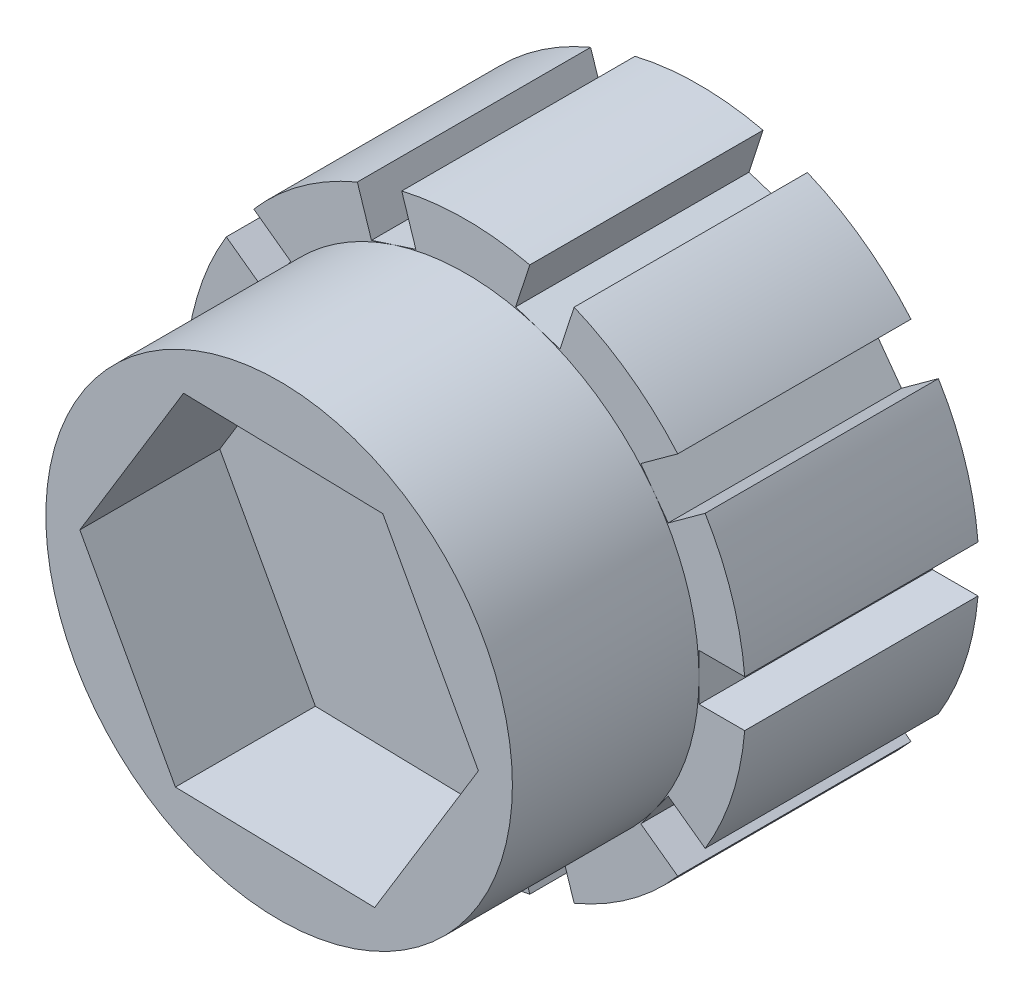
SolidWorks part; units mm, degrees
ref_plane "Front Plane" through (0, 0, 0) normal (0, 0, 1) x (1, 0, 0)
ref_plane "Top Plane" through (0, 0, 0) normal (0, 1, 0) x (1, 0, 0)
ref_plane "Right Plane" through (0, 0, 0) normal (1, 0, 0) x (0, 0, -1)
sketch "Sketch1" plane through (0, 0, 0) normal (0, 0, 1) x (1, 0, 0)
  circle A0 centre (0, 0) radius 6
  dimension "D1" = 12
extrude "Boss-Extrude1" add sketch "Sketch1" along normal blind 5
sketch "Sketch2" plane through (0, 0, 5) normal (0, 0, 1) x (1, 0, 0)
  circle A0 centre (0, 0) radius 5
  dimension "D1" = 10
extrude "Boss-Extrude2" add sketch "Sketch2" along normal blind 4
sketch "Sketch3" plane through (0, 0, 9) normal (0, 0, 1) x (1, 0, 0)
  line L1 (2.0482, -3.7494) -> (4.2712, -0.1009)
  line L2 (4.2712, -0.1009) -> (2.223, 3.6485)
  line L3 (2.223, 3.6485) -> (-2.0482, 3.7494)
  line L4 (-2.0482, 3.7494) -> (-4.2712, 0.1009)
  line L5 (-4.2712, 0.1009) -> (-2.223, -3.6485)
  line L6 (-2.223, -3.6485) -> (2.0482, -3.7494)
  circle A0 centre (0, 0) radius 3.7 construction
  dimension "D1" = 7.4
extrude "Cut-Extrude1" cut sketch "Sketch3" against normal blind 3
sketch "Sketch4" plane through (0, 0, 0) normal (0, 0, -1) x (-1, 0, 0)
  line L0 (0, 0) -> (6, 0) construction
  line L1 (6, 0) -> (6, -2.1157) construction
  line L2 (5.957, -3.71) -> (5.3692, -4.519)
  line L3 (7, 0.5) -> (5, 0.5)
  line L4 (7, 0.5) -> (7, -0.5)
  line L5 (7, -0.5) -> (5, -0.5)
  line L6 (5, 0.5) -> (5, -0.5)
  line L7 (7, 0.5) -> (5, -0.5) construction
  line L8 (7, -0.5) -> (5, 0.5) construction
  line L9 (5.957, -3.71) -> (4.339, -2.5344)
  line L10 (4.339, -2.5344) -> (3.7512, -3.3434)
  line L11 (5.3692, -4.519) -> (3.7512, -3.3434)
  line L12 (2.6386, -6.5029) -> (1.6876, -6.8119)
  line L13 (2.6386, -6.5029) -> (2.0206, -4.6008)
  line L14 (2.0206, -4.6008) -> (1.0696, -4.9098)
  line L15 (1.6876, -6.8119) -> (1.0696, -4.9098)
  line L16 (-1.6876, -6.8119) -> (-2.6386, -6.5029)
  line L17 (-1.6876, -6.8119) -> (-1.0696, -4.9098)
  line L18 (-1.0696, -4.9098) -> (-2.0206, -4.6008)
  line L19 (-2.6386, -6.5029) -> (-2.0206, -4.6008)
  line L20 (-5.3692, -4.519) -> (-5.957, -3.71)
  line L21 (-5.3692, -4.519) -> (-3.7512, -3.3434)
  line L22 (-3.7512, -3.3434) -> (-4.339, -2.5344)
  line L23 (-5.957, -3.71) -> (-4.339, -2.5344)
  line L24 (-7, -0.5) -> (-7, 0.5)
  line L25 (-7, -0.5) -> (-5, -0.5)
  line L26 (-5, -0.5) -> (-5, 0.5)
  line L27 (-7, 0.5) -> (-5, 0.5)
  line L28 (-5.957, 3.71) -> (-5.3692, 4.519)
  line L29 (-5.957, 3.71) -> (-4.339, 2.5344)
  line L30 (-4.339, 2.5344) -> (-3.7512, 3.3434)
  line L31 (-5.3692, 4.519) -> (-3.7512, 3.3434)
  line L32 (-2.6386, 6.5029) -> (-1.6876, 6.8119)
  line L33 (-2.6386, 6.5029) -> (-2.0206, 4.6008)
  line L34 (-2.0206, 4.6008) -> (-1.0696, 4.9098)
  line L35 (-1.6876, 6.8119) -> (-1.0696, 4.9098)
  line L36 (1.6876, 6.8119) -> (2.6386, 6.5029)
  line L37 (1.6876, 6.8119) -> (1.0696, 4.9098)
  line L38 (1.0696, 4.9098) -> (2.0206, 4.6008)
  line L39 (2.6386, 6.5029) -> (2.0206, 4.6008)
  line L40 (5.3692, 4.519) -> (5.957, 3.71)
  line L41 (5.3692, 4.519) -> (3.7512, 3.3434)
  line L42 (3.7512, 3.3434) -> (4.339, 2.5344)
  line L43 (5.957, 3.71) -> (4.339, 2.5344)
  circle A0 centre (0, 0) radius 6 construction
  point P89 (0, 0)
  dimension "D1" = 1
  dimension "D2" = 1
  dimension "D3" = 10
extrude "Cut-Extrude2" cut sketch "Sketch4" against normal blind 10
